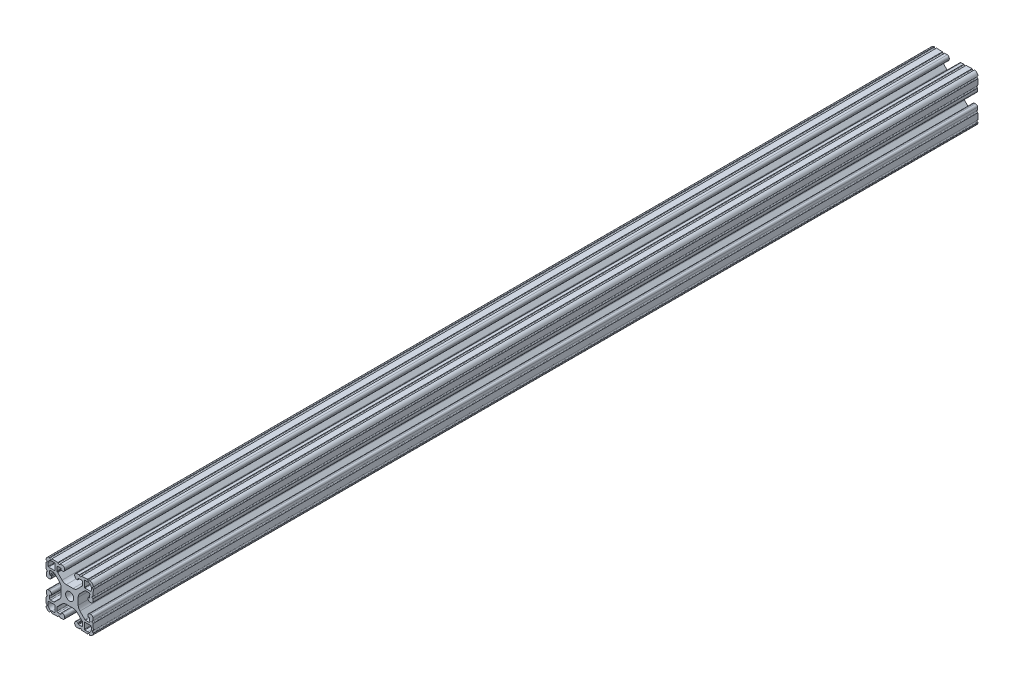
SolidWorks part; units mm, degrees
ref_plane "Front Plane" through (0, 0, 0) normal (0, 0, 1) x (1, 0, 0)
ref_plane "Top Plane" through (0, 0, 0) normal (0, 1, 0) x (1, 0, 0)
ref_plane "Right Plane" through (0, 0, 0) normal (1, 0, 0) x (0, 0, -1)
sketch "Sketch2" plane through (0, 0, 0) normal (0, 0, 1) x (1, 0, 0)
  line L0 (0, 19.05) -> (0, -19.05) construction
  line L1 (-19.05, 0) -> (19.05, 0) construction
  line L2 (4.064, -19.05) -> (19.05, -19.05) construction
  line L3 (19.05, -19.05) -> (19.05, -4.064) construction
  line L4 (4.064, -19.05) -> (4.064, -15.8768) construction
  line L5 (4.064, -15.8768) -> (13.7215, -15.8768) construction
  line L6 (13.7215, -15.8768) -> (4.7027, -6.858) construction
  line L7 (0, 0) -> (19.05, -19.05) construction
  line L8 (19.05, -4.064) -> (15.8768, -4.064) construction
  line L9 (15.8768, -4.064) -> (15.8768, -13.7215) construction
  line L10 (15.8768, -13.7215) -> (6.858, -4.7027) construction
  line L11 (11.3674, -9.2121) -> (9.2121, -11.3674) construction
  line L12 (10.287, -12.4423) -> (10.287, -15.8768) construction
  line L13 (15.7642, -19.0481) -> (4.064, -18.6395) construction
  line L14 (4.064, -18.6395) -> (4.2014, -14.7049) construction
  line L15 (4.2014, -14.7049) -> (6.858, -14.7977) construction
  line L16 (6.858, -14.7977) -> (6.858, -15.8768) construction
  line L17 (19.05, 4.064) -> (19.05, -4.064) construction
  line L18 (-19.05, -19.05) -> (19.05, -19.05) construction
  line L19 (-19.05, -19.05) -> (-19.05, 19.05) construction
  line L20 (-19.05, 19.05) -> (19.05, 19.05) construction
  line L21 (19.05, -19.05) -> (19.05, 19.05) construction
  line L22 (8.5725, -18.7969) -> (8.6004, -17.9973) construction
  line L23 (15.24, -19.0298) -> (15.2679, -18.2301) construction
  circle A0 centre (0, 0) radius 3.2639 construction
  arc A1 (18.1201, -18.1201) -> (15.7642, -19.0481) centre (15.875, -15.875) cw construction
  point P8 (0, -6.858)
  point P16 (10.2898, -10.2898)
  point P28 (11.8872, -11.8872)
  point P34 (8.5725, -18.7969)
  point P36 (15.24, -19.0298)
  point P38 (19.05, 0)
  dimension "D7" = 1.6002
  dimension "Center Hole Diameter" = 6.5278
  dimension "Corner Radius" = 3.175
  dimension "Slot Depth" = 12.192
  dimension "D1" = 3.048
  dimension "D3" = 2
  dimension "Flange Thickness" = 3.937
  dimension "D4" = 3.1732
  dimension "D2" = 20.574
  dimension "D5" = 13.716
  dimension "D6" = 7.1628
  dimension "D8" = 15.24
  dimension "D9" = 8.5725
  dimension "D10" = 0.8001
  dimension "Rail Height" = 38.1
  dimension "Rail Width" = 38.1
  dimension "T Slot Width" = 8.128
sketch "Sketch3" plane through (0, 0, 0) normal (1, 0, 0) x (0, 0, -1)
  line L0 (-355.6, 19.05) -> (355.6, 19.05) construction
  line L1 (-304.8, 0) -> (304.8, 0) construction
  dimension "Length" = 711.2
  dimension "D1" = 50.8
sketch "Sketch4" plane through (0, 0, 0) normal (0, 0, 1) x (1, 0, 0)
  line L1 (6.858, -14.7977) -> (6.858, -15.8768) construction
  line L2 (11.8872, -12.2682) -> (11.8872, -16.9436)
  line L3 (12.2549, -17.3243) -> (14.4454, -17.4008)
  line L7 (12.2682, -11.8872) -> (16.9436, -11.8872)
  line L9 (17.3243, -12.2549) -> (17.4008, -14.4454)
  line L22 (0, 0) -> (19.05, -19.05) construction
  line L23 (15.7642, -19.0481) -> (5.5961, -18.693)
  line L24 (4.064, -17.1065) -> (4.064, -16.344)
  line L25 (5.7069, -14.7575) -> (6.4903, -14.7848)
  line L26 (6.858, -15.1656) -> (6.858, -15.6891)
  line L27 (7.2257, -16.0699) -> (9.4655, -16.1481)
  line L28 (10.287, -15.3549) -> (10.287, -12.771)
  line L29 (10.0545, -12.2098) -> (6.0939, -8.2492)
  line L30 (2.7353, -6.858) -> (0, -6.858)
  line L31 (13.7215, -15.8768) -> (4.7027, -6.858) construction
  line L32 (4.064, -19.05) -> (19.05, -19.05) construction
  line L33 (4.064, -19.05) -> (4.064, -15.8768) construction
  line L34 (0, 19.05) -> (0, -19.05) construction
  line L35 (0, -3.2639) -> (0, -6.858)
  line L36 (0, 0) -> (19.1669, -19.1669) construction
  line L46 (10.287, -12.4423) -> (10.287, -15.8768) construction
  line L47 (6.858, -2.7353) -> (6.858, 0)
  line L48 (12.2098, -10.0545) -> (8.2492, -6.0939)
  line L49 (15.3549, -10.287) -> (12.771, -10.287)
  line L50 (16.0699, -7.2257) -> (16.1481, -9.4655)
  line L51 (15.1656, -6.858) -> (15.6891, -6.858)
  line L52 (14.7575, -5.7069) -> (14.7848, -6.4903)
  line L53 (17.1065, -4.064) -> (16.344, -4.064)
  line L54 (19.0481, -15.7642) -> (18.693, -5.5961)
  line L55 (3.2639, 0) -> (6.858, 0)
  arc A1 (14.4454, -17.4008) -> (17.4008, -14.4454) centre (14.5451, -14.5451) ccw
  arc A10 (16.9436, -11.8872) -> (17.3243, -12.2549) centre (16.9436, -12.2682) cw
  arc A12 (19.0481, -15.7642) -> (15.7642, -19.0481) centre (15.875, -15.875) cw
  arc A13 (3.2639, 0) -> (0, -3.2639) centre (0, 0) cw
  circle A14 centre (0, 0) radius 3.2639 construction
  arc A16 (6.0939, -8.2492) -> (2.7353, -6.858) centre (2.7353, -11.6078) ccw
  arc A17 (5.5961, -18.693) -> (4.064, -17.1065) centre (5.6515, -17.1065) cw
  arc A18 (4.064, -16.344) -> (5.7069, -14.7575) centre (5.6515, -16.344) cw
  arc A19 (9.4655, -16.1481) -> (10.287, -15.3549) centre (9.4933, -15.3549) ccw
  arc A20 (10.287, -12.771) -> (10.0545, -12.2098) centre (9.4933, -12.771) ccw
  arc A21 (6.4903, -14.7848) -> (6.858, -15.1656) centre (6.477, -15.1656) cw
  arc A22 (6.858, -15.6891) -> (7.2257, -16.0699) centre (7.239, -15.6891) ccw
  arc A23 (15.6891, -6.858) -> (16.0699, -7.2257) centre (15.6891, -7.239) cw
  arc A24 (14.7848, -6.4903) -> (15.1656, -6.858) centre (15.1656, -6.477) ccw
  arc A25 (12.771, -10.287) -> (12.2098, -10.0545) centre (12.771, -9.4933) cw
  arc A26 (16.1481, -9.4655) -> (15.3549, -10.287) centre (15.3549, -9.4933) cw
  arc A27 (16.344, -4.064) -> (14.7575, -5.7069) centre (16.344, -5.6515) ccw
  arc A28 (18.693, -5.5961) -> (17.1065, -4.064) centre (17.1065, -5.6515) ccw
  arc A29 (8.2492, -6.0939) -> (6.858, -2.7353) centre (11.6078, -2.7353) cw
  arc A30 (15.7642, -19.0481) -> (18.1201, -18.1201) centre (15.875, -15.875) ccw construction
  arc A31 (11.8872, -12.2682) -> (12.2682, -11.8872) centre (12.2682, -12.2682) cw
  arc A32 (11.8872, -16.9436) -> (12.2549, -17.3243) centre (12.2682, -16.9436) ccw
  point P33 (4.064, -18.6395)
  point P42 (6.858, -4.7027)
  point P45 (4.7027, -6.858)
  point P76 (18.6395, -4.064)
  point P89 (11.8872, -11.8872)
  dimension "D2" = 4.7498
  dimension "D3" = 0.7937
  dimension "D5" = 0.381
  dimension "D6" = 1.5875
  dimension "D8" = 2.8575
  dimension "D1" = 2
  dimension "D4" = 2.6784
  dimension "D7" = 1.6002
extrude "Boss-Extrude1" add sketch "Sketch4" along normal mid plane 711.2
sketch "Sketch8" plane through (0, 0, 0) normal (0, 0, 1) x (1, 0, 0)
  line L0 (7.6492, -18.7647) -> (9.4958, -18.8292)
  line L1 (15.7642, -19.0481) -> (4.064, -18.6395) construction
  line L2 (9.4958, -18.8292) -> (9.2789, -18.4213)
  line L3 (7.894, -18.3729) -> (7.6492, -18.7647)
  line L4 (8.5725, -18.7969) -> (8.6004, -17.9973) construction
  line L5 (14.3167, -18.9975) -> (16.1633, -19.062)
  line L7 (16.1633, -19.062) -> (15.9464, -18.6541)
  line L8 (14.5615, -18.6058) -> (14.3167, -18.9975)
  line L9 (15.24, -19.0298) -> (15.2679, -18.2301) construction
  line L10 (0, 0) -> (19.05, -19.05) construction
  line L11 (18.6058, -14.5615) -> (18.9975, -14.3167)
  line L12 (19.062, -16.1633) -> (18.6541, -15.9464)
  line L13 (18.9975, -14.3167) -> (19.062, -16.1633)
  line L14 (18.3729, -7.894) -> (18.7647, -7.6492)
  line L15 (18.8292, -9.4958) -> (18.4213, -9.2789)
  line L16 (18.7647, -7.6492) -> (18.8292, -9.4958)
  arc A0 (9.2789, -18.4213) -> (7.894, -18.3729) centre (8.5725, -18.7969) ccw
  arc A1 (15.9464, -18.6541) -> (14.5615, -18.6058) centre (15.24, -19.0298) ccw
  arc A2 (18.6541, -15.9464) -> (18.6058, -14.5615) centre (19.0298, -15.24) cw
  arc A3 (18.4213, -9.2789) -> (18.3729, -7.894) centre (18.7969, -8.5725) cw
  dimension "D1" = 60
extrude "Cut-Extrude2" cut sketch "Sketch8" against normal through all both and the other way through all
mirror "Mirror1" about plane through (0, 0, 0) normal (1, 0, 0) of bodies 142 134
mirror "Mirror2" about plane through (0, 0, 0) normal (0, 1, 0) of bodies 135
sketch "Sketch5" plane through (0, 0, 0) normal (0, 0, 1) x (1, 0, 0)
  line L0 (-6.0939, 8.2492) -> (-10.0545, 12.2098) construction
  line L1 (-10.1338, 12.508) -> (-10.1338, 12)
  line L2 (-9.9645, 11.8306) -> (-9.6506, 11.8306)
  line L3 (-9.6506, 11.8306) -> (-9.6506, 12.508)
  line L4 (-9.6506, 12.508) -> (-10.1338, 12.508)
  line L5 (-9.9046, 12.0598) -> (-9.9645, 12) construction
  circle A0 centre (-9.9046, 12.0598) radius 0.254 construction
  arc A1 (-10.287, 12.771) -> (-10.0545, 12.2098) centre (-9.4933, 12.771) ccw construction
  arc A2 (-10.1338, 12) -> (-9.9645, 11.8306) centre (-9.9645, 12) ccw
  dimension "D2" = 0.508
  dimension "D3" = 0.1693
  dimension "D1" = 0.7112
  dimension "D4" = 0.508
extrude "Cut-Extrude1" cut sketch "Sketch5" against normal through all both and the other way through all
ref_plane "Plane1" through (0, 19.05, 0) normal (0, 1, 0) x (-1, 0, 0)
ref_plane "Plane2" through (19.05, 0, 0) normal (1, 0, 0) x (0, 0, -1)
ref_plane "Plane3" through (0, -19.05, 0) normal (0, -1, 0) x (1, 0, 0)
ref_plane "Plane4" through (-19.05, 0, 0) normal (-1, 0, 0) x (0, 0, 1)
equation "\"D1@Boss-Extrude1\"=\"Length@Sketch3\""
equation "\"D6@Sketch4\"=\"Corner Radius@Sketch2\"/2"
equation "\"D3@Sketch4\"=\"D6@Sketch4\"/2"
equation "\"D4@Sketch2\"=\"Flange Thickness@Sketch2\"*.806"
equation "\"D7@Sketch4\"=\"D7@Sketch2\""
equation "\"D8@Sketch4\"=\"Corner Radius@Sketch2\"*.9"
equation "\"D3@Sketch5\"=\"D2@Sketch5\"/3"
equation "\"D4@Sketch5\"=\"D2@Sketch5\""
equation "\"D8@Sketch2\"=\"Rail Width@Sketch2\"*.4"
equation "\"D9@Sketch2\"=\"Rail Width@Sketch2\"*.225"
equation "\"D10@Sketch2\"=\"D7@Sketch2\"/2"
